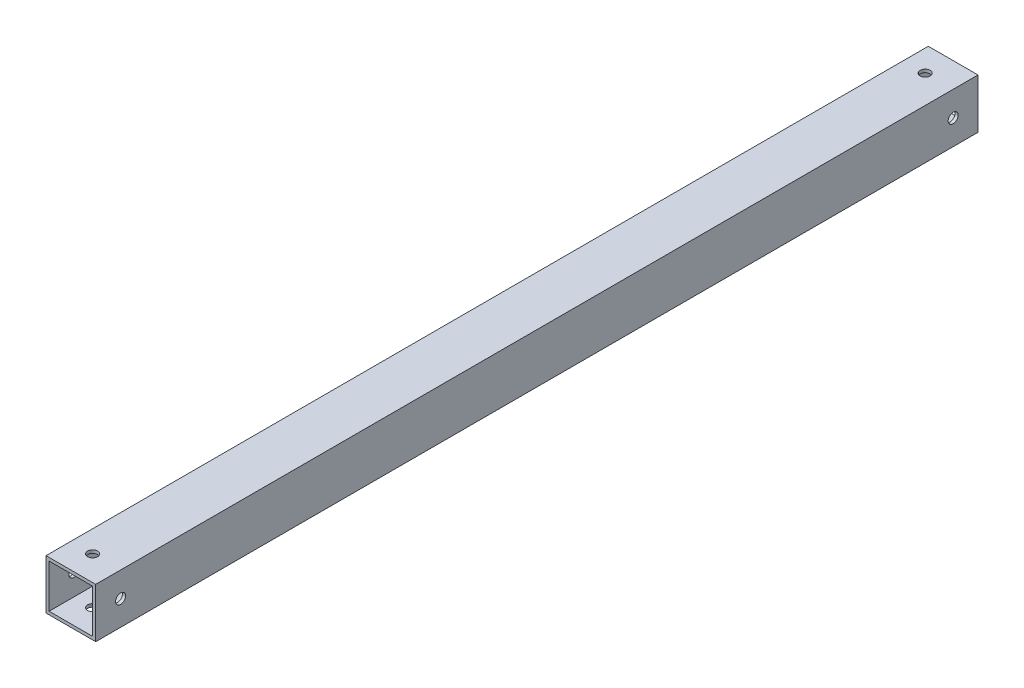
SolidWorks part; units mm, degrees
ref_plane "Front Plane" through (0, 0, 0) normal (0, 0, 1) x (1, 0, 0)
ref_plane "Top Plane" through (0, 0, 0) normal (0, 1, 0) x (1, 0, 0)
ref_plane "Right Plane" through (0, 0, 0) normal (1, 0, 0) x (0, 0, -1)
sketch "Sketch1" plane through (0, 0, 0) normal (0, 0, 1) x (1, 0, 0)
  line L1 (0, 0) -> (25.4, 0)
  line L2 (0, 0) -> (0, 25.4)
  line L3 (0, 25.4) -> (25.4, 25.4)
  line L4 (25.4, 0) -> (25.4, 25.4)
  line L5 (1.5875, 1.5875) -> (23.8125, 1.5875)
  line L6 (1.5875, 1.5875) -> (1.5875, 23.8125)
  line L7 (1.5875, 23.8125) -> (23.8125, 23.8125)
  line L8 (23.8125, 1.5875) -> (23.8125, 23.8125)
  dimension "D1" = 25.4
  dimension "D2" = 1.5875
  dimension "D3" = 1.5875
  dimension "D4" = 1.5875
  dimension "D5" = 1.5875
extrude "Boss-Extrude1" add sketch "Sketch1" along normal blind 450.85
sketch "Sketch4" plane through (25.4, 0, 0) normal (1, 0, 0) x (0, 0, -1)
  line L0 (-450.85, 25.4) -> (0, 25.4) construction
  line L1 (-450.85, 0) -> (-450.85, 25.4) construction
  line L2 (-225.425, 25.4) -> (-225.425, 0) construction
  line L3 (-450.85, 0) -> (0, 0) construction
  circle A0 centre (-438.15, 12.7) radius 2.54
  circle A13 centre (-12.7, 12.7) radius 2.54
  dimension "D1" = 5.08
  dimension "D2" = 12.7
  dimension "D3" = 12.7
extrude "Cut-Extrude3" cut sketch "Sketch4" against normal through all
sketch "Sketch5" plane through (0, 0, 0) normal (0, -1, 0) x (1, 0, 0)
  line L0 (25.4, 225.425) -> (0, 225.425) construction
  line L1 (25.4, 450.85) -> (25.4, 0) construction
  line L2 (0, 450.85) -> (0, 0) construction
  line L3 (0, 450.85) -> (25.4, 450.85) construction
  circle A0 centre (11.1125, 438.15) radius 2.54
  circle A1 centre (11.1125, 12.7) radius 2.54
  dimension "D1" = 5.08
  dimension "D2" = 12.7
  dimension "D3" = 14.2875
extrude "Cut-Extrude4" cut sketch "Sketch5" against normal through all
